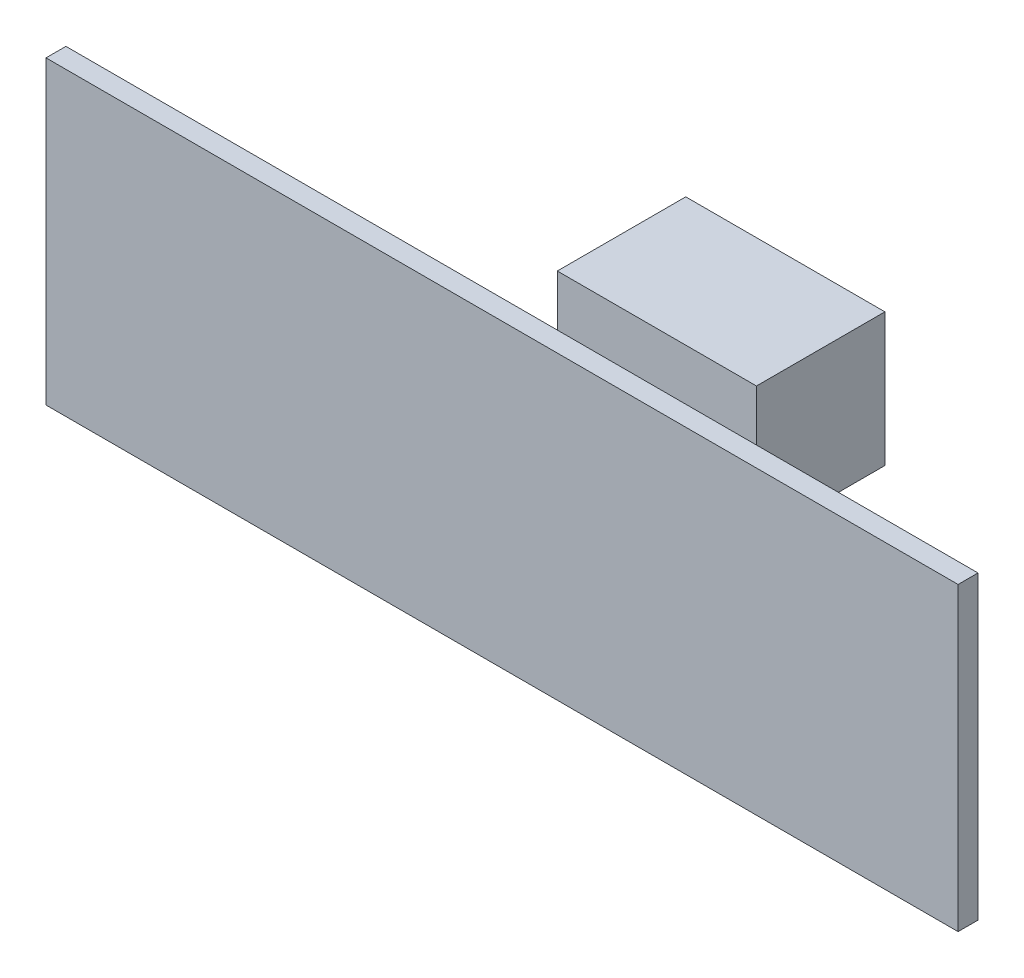
SolidWorks part; units mm, degrees
ref_plane "Front Plane" through (0, 0, 0) normal (0, 0, 1) x (1, 0, 0)
ref_plane "Top Plane" through (0, 0, 0) normal (0, 1, 0) x (1, 0, 0)
ref_plane "Right Plane" through (0, 0, 0) normal (1, 0, 0) x (0, 0, -1)
ref_plane "further z plane" through (0, 0, 25.4) normal (0, 0, 1) x (1, 0, 0)
sketch "Sketch2" plane through (0, 0, 25.4) normal (0, 0, 1) x (1, 0, 0)
  line L1 (-58.1634, -19.1747) -> (58.1634, -19.1747)
  line L2 (-58.1634, -19.1747) -> (-58.1634, 19.1747)
  line L3 (-58.1634, 19.1747) -> (58.1634, 19.1747)
  line L4 (58.1634, -19.1747) -> (58.1634, 19.1747)
  line L5 (-58.1634, -19.1747) -> (58.1634, 19.1747) construction
  line L6 (-58.1634, 19.1747) -> (58.1634, -19.1747) construction
  point P0 (0, 0)
extrude "out in z direction" add sketch "Sketch2" along normal blind 2.54 separate body
sketch "Sketch3" plane through (0, 0, 0) normal (1, 0, 0) x (0, 0, -1)
  line L1 (-8.191, -8.49) -> (8.191, -8.49)
  line L2 (-8.191, -8.49) -> (-8.191, 8.49)
  line L3 (-8.191, 8.49) -> (8.191, 8.49)
  line L4 (8.191, -8.49) -> (8.191, 8.49)
  line L5 (-8.191, -8.49) -> (8.191, 8.49) construction
  line L6 (-8.191, 8.49) -> (8.191, -8.49) construction
  point P0 (0, 0)
extrude "at origin" add sketch "Sketch3" along normal mid plane 25.4 separate body
